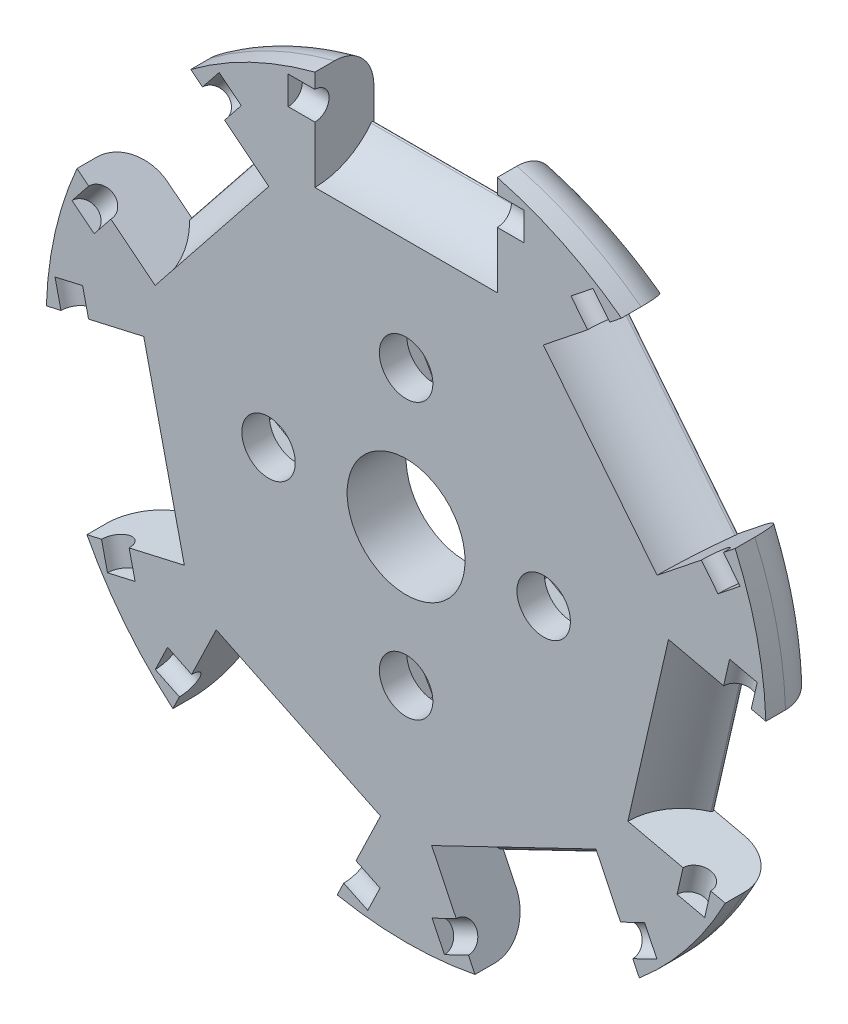
SolidWorks part; units mm, degrees
other "Markup1"
sketch "Sketch8" plane through (32.7336, 32.7336, 0) normal (0.5701, 0.1846, 0.8006) x (0.8043, 0.0736, -0.5897)
ref_plane "Front Plane" through (0, 0, 0) normal (0, 0, 1) x (1, 0, 0)
ref_plane "Top Plane" through (0, 0, 0) normal (0, 1, 0) x (1, 0, 0)
ref_plane "Right Plane" through (0, 0, 0) normal (1, 0, 0) x (0, 0, -1)
sketch "Sketch1" plane through (0, 0, 0) normal (0, 0, 1) x (1, 0, 0)
  circle A0 centre (0, 0) radius 29.0703
  dimension "D1" = 58.1406
extrude "Boss-Extrude2" add sketch "Sketch1" against normal blind 4.7625
fillet "Fillet1" radius 3.175 1 edges at (29.0703, 0, -4.7625)
sketch "Sketch2" plane through (0, 0, 0) normal (0, 0, 1) x (1, 0, 0)
  line L1 (-12.7, 29.0703) -> (12.7, 29.0703) construction
  line L2 (-7.366, 30.3403) -> (7.366, 30.3403)
  line L3 (-7.366, 30.3403) -> (-7.366, 19.9263)
  line L4 (-7.366, 19.9263) -> (7.366, 19.9263)
  line L5 (7.366, 30.3403) -> (7.366, 19.9263)
  line L6 (-7.366, 30.3403) -> (7.366, 19.9263) construction
  line L7 (-7.366, 19.9263) -> (7.366, 30.3403) construction
  line L35 (0, 0) -> (0, 29.0703) construction
  circle A1 centre (0, 0) radius 29.0703 construction
  point P10 (0, 25.1333)
  circle M7 centre (0, 0) radius 29.0703
  dimension "D1" = 14.732
  dimension "D2" = 10.414
  dimension "D3" = 1.27
  dimension "D4" = 25.4
extrude "Cut-Extrude2" cut sketch "Sketch2" against normal blind 12.7 contours L5 L3 L4 M7
pattern_circular "CirPattern1" count 7 over 360 about axis through (0, 0, 0) along (0, 0, 1) of "Cut-Extrude2"
ref_plane "Plane1" through (0, 0, 0) normal (1, 0, 0) x (0, 0, -1)
sketch "Sketch4" plane through (0, 0, 0) normal (1, 0, 0) x (0, 0, -1)
  line L0 (4.7625, 19.9263) -> (0, 19.9263) construction
  circle A0 centre (0, 25.7683) radius 1.143
  dimension "D1" = 2.286
  dimension "D2" = 5.842
extrude "Cut-Extrude4" cut sketch "Sketch4" against normal mid plane 19.05
pattern_circular "CirPattern2" count 7 over 360 about axis through (0, 0, 0) along (0, 0, 1) of "Cut-Extrude4"
sketch "Sketch5" plane through (0, 0, 0) normal (0, 0, 1) x (1, 0, 0)
  circle A0 centre (0, 0) radius 4.7625
  dimension "D1" = 9.525
sketch "Sketch6" plane through (0, 0, -4.7625) normal (0, 0, -1) x (-1, 0, 0)
  circle A1 centre (11.1125, 0) radius 2.159
  circle A4 centre (0, -11.1125) radius 2.159
  circle A5 centre (-11.1125, 0) radius 2.159
  circle A6 centre (0, 11.1125) radius 2.159
  point P12 (0, 0)
  dimension "D4" = 4.318
  dimension "D1" = 11.1125
  dimension "D2" = 4
extrude "Cut-Extrude7" cut sketch "Sketch6" against normal through all
sketch "Sketch10" plane through (7.366, 0, 0) normal (-1, 0, 0) x (0, 0, 1)
  line L0 (-4.7625, 24.8256) -> (-4.7625, 19.9263) construction
  line L1 (-4.7625, 19.9263) -> (0, 19.9263)
  line L2 (-4.7625, 19.9263) -> (-4.7625, 22.6092)
  line L4 (0, 19.9263) -> (0, 20.0533)
  arc A0 (-4.7625, 22.6092) -> (0, 20.0533) centre (0, 25.7683) ccw
  dimension "D1" = 11.43
  dimension "D2" = 4.7625
extrude "Boss-Extrude4" add sketch "Sketch10" along normal up to next
fillet "Fillet2" radius 0.127 1 edges at (0, 22.6092, -4.7625)
pattern_circular "CirPattern5" count 7 over 360 about axis through (0, 0, 0) along (0, 0, 1) of "Boss-Extrude4", "Fillet2"
extrude "Cut-Extrude9" cut sketch "Sketch5" against normal up to next
sketch "Sketch7" plane through (0, 0, -4.7625) normal (0, 0, -1) x (-1, 0, 0)
  line L0 (15.5575, -2.5663) -> (15.5575, 2.5663)
  line L1 (2.5663, 15.5575) -> (-2.5663, 15.5575)
  line L2 (-2.5663, 15.5575) -> (-5.1326, 11.1125)
  line L3 (-5.1326, 11.1125) -> (-2.5663, 6.6675)
  line L4 (-2.5663, 6.6675) -> (2.5663, 6.6675)
  line L5 (2.5663, 6.6675) -> (5.1326, 11.1125)
  line L6 (5.1326, 11.1125) -> (2.5663, 15.5575)
  line L7 (15.5575, 2.5663) -> (11.1125, 5.1326)
  line L8 (11.1125, 5.1326) -> (6.6675, 2.5663)
  line L9 (6.6675, 2.5663) -> (6.6675, -2.5663)
  line L10 (6.6675, -2.5663) -> (11.1125, -5.1326)
  line L11 (11.1125, -5.1326) -> (15.5575, -2.5663)
  line L12 (-2.5663, -15.5575) -> (2.5663, -15.5575)
  line L13 (2.5663, -15.5575) -> (5.1326, -11.1125)
  line L14 (5.1326, -11.1125) -> (2.5663, -6.6675)
  line L15 (2.5663, -6.6675) -> (-2.5663, -6.6675)
  line L16 (-2.5663, -6.6675) -> (-5.1326, -11.1125)
  line L17 (-5.1326, -11.1125) -> (-2.5663, -15.5575)
  line L18 (-15.5575, 2.5663) -> (-15.5575, -2.5663)
  line L19 (-15.5575, -2.5663) -> (-11.1125, -5.1326)
  line L20 (-11.1125, -5.1326) -> (-6.6675, -2.5663)
  line L21 (-6.6675, -2.5663) -> (-6.6675, 2.5663)
  line L22 (-6.6675, 2.5663) -> (-11.1125, 5.1326)
  line L23 (-11.1125, 5.1326) -> (-15.5575, 2.5663)
  circle A9 centre (0, 11.1125) radius 4.445 construction
  point P15 (0, 0)
  point P35 (0, 0)
  dimension "D1" = 8.89
  dimension "D2" = 11.1125
  dimension "D3" = 5.1326
  dimension "D4" = 4
extrude "Cut-Extrude8" cut sketch "Sketch7" against normal blind 2.54 and the other way through all
